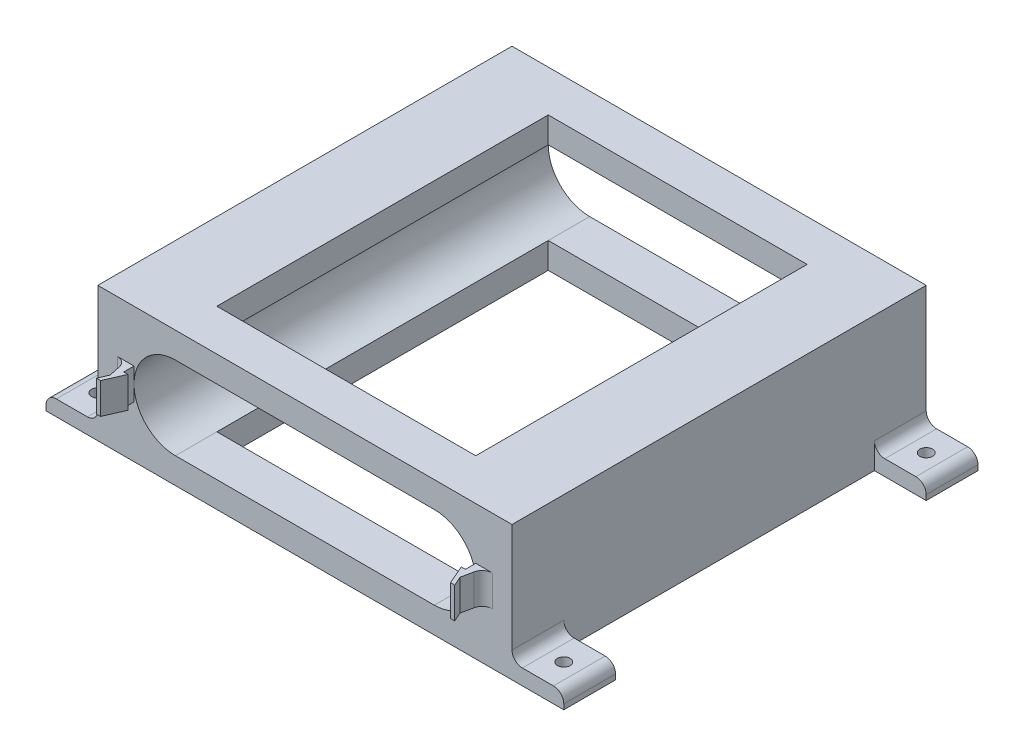
SolidWorks part; units mm, degrees
ref_plane "Front Plane" through (0, 0, 0) normal (0, 0, 1) x (1, 0, 0)
ref_plane "Top Plane" through (0, 0, 0) normal (0, 1, 0) x (1, 0, 0)
ref_plane "Right Plane" through (0, 0, 0) normal (1, 0, 0) x (0, 0, -1)
sketch "Sketch1" plane through (0, 0, 0) normal (0, 0, 1) x (1, 0, 0)
  line L0 (-31.75, 0) -> (31.75, 0) construction
  line L1 (-31.75, 10.16) -> (31.75, 10.16)
  line L2 (-31.75, -10.16) -> (31.75, -10.16)
  line L3 (0, 0) -> (0, 43.3007) construction
  line L4 (50.8, 16.51) -> (-50.8, 16.51)
  line L5 (50.8, 16.51) -> (50.8, -16.51)
  line L6 (50.8, -16.51) -> (-50.8, -16.51)
  line L7 (-50.8, 16.51) -> (-50.8, -16.51)
  arc A0 (-31.75, 10.16) -> (-31.75, -10.16) centre (-31.75, 0) ccw
  arc A1 (31.75, -10.16) -> (31.75, 10.16) centre (31.75, 0) ccw
  point P3 (0, 0)
  point P8 (0, 0)
  point P13 (0, 16.51)
  dimension "D2" = 10.16
  dimension "D3" = 19.05
  dimension "D1" = 63.5
  dimension "D4" = 6.35
  dimension "D5" = 6.35
extrude "Boss-Extrude1" add sketch "Sketch1" against normal blind 101.6
sketch "Sketch2" plane through (0, 16.51, 0) normal (0, 1, 0) x (1, 0, 0)
  line L0 (0, 10.16) -> (0, 91.44) construction
  line L1 (-31.75, 91.44) -> (31.75, 91.44)
  line L2 (-31.75, 91.44) -> (-31.75, 10.16)
  line L3 (-31.75, 10.16) -> (31.75, 10.16)
  line L4 (31.75, 91.44) -> (31.75, 10.16)
  line L5 (50.8, 101.6) -> (-50.8, 101.6) construction
  line L6 (50.8, 0) -> (-50.8, 0) construction
  line L7 (31.75, 101.6) -> (31.75, 0) construction
  point P4 (0, 10.16)
  dimension "D1" = 10.16
  dimension "D2" = 10.16
extrude "Cut-Extrude1" cut sketch "Sketch2" against normal through all
ref_plane "Plane1" through (0, 0, 0) normal (0, 1, 0) x (1, 0, 0)
sketch "Sketch3" plane through (0, 16.51, 0) normal (0, 1, 0) x (1, 0, 0)
  line L1 (-42.926, -4.8679) -> (-43.942, -7.1959)
  line L2 (-43.942, -7.1959) -> (-42.926, -7.1959)
  line L3 (-42.926, -7.1959) -> (-41.91, -4.8679)
  line L8 (-40.894, -2.54) -> (-41.91, -4.8679)
  line L9 (-40.894, -2.54) -> (-41.91, -2.54)
  line L10 (-42.926, -4.8679) -> (-43.942, 0)
  line L11 (-42.926, -2.54) -> (-41.91, -2.54) construction
  line L12 (-41.91, -2.54) -> (-41.91, 0)
  line L13 (50.8, 0) -> (-50.8, 0) construction
  line L14 (-41.91, 101.6) -> (-41.91, 0) construction
  line L15 (-43.942, 0) -> (-41.91, 0)
  line L16 (-42.926, -4.8679) -> (-42.926, 0) construction
  point P3 (-44.2626, 0)
  point P6 (-42.9703, -4.8481)
  dimension "D1" = 1.016
  dimension "D2" = 2.54
  dimension "D3" = 1.016
extrude "Boss-Extrude2" add sketch "Sketch3" along normal mid plane 7.62 from surface at -16.51 starting at plane "Plane1"
fillet "Fillet2" radius 2.54 1 edges at (-43.942, 0, 0)
sketch "Sketch4" plane through (0, -16.51, 0) normal (0, -1, 0) x (1, 0, 0)
  line L0 (0, 0) -> (0, -101.6) construction
  line L1 (-50.8, 0) -> (-63.5, 0)
  line L2 (-50.8, 0) -> (-50.8, -12.7)
  line L3 (-50.8, -12.7) -> (-63.5, -12.7)
  line L4 (-63.5, 0) -> (-63.5, -12.7)
  line L5 (-50.8, -101.6) -> (50.8, -101.6) construction
  line L6 (-50.8, -50.8) -> (50.8, -50.8) construction
  line L7 (-50.8, -101.6) -> (-50.8, 0) construction
  line L8 (50.8, -101.6) -> (50.8, 0) construction
  line L9 (-63.5, -101.6) -> (-63.5, -88.9)
  line L10 (-50.8, -88.9) -> (-63.5, -88.9)
  line L11 (-50.8, -101.6) -> (-50.8, -88.9)
  line L12 (-50.8, -101.6) -> (-63.5, -101.6)
  line L13 (50.8, -101.6) -> (63.5, -101.6)
  line L14 (50.8, -101.6) -> (50.8, -88.9)
  line L15 (50.8, -88.9) -> (63.5, -88.9)
  line L16 (63.5, -101.6) -> (63.5, -88.9)
  line L17 (63.5, 0) -> (63.5, -12.7)
  line L18 (50.8, -12.7) -> (63.5, -12.7)
  line L19 (50.8, 0) -> (50.8, -12.7)
  line L20 (50.8, 0) -> (63.5, 0)
  line L21 (-63.5, 0) -> (-50.8, -12.7) construction
  circle A0 centre (-57.15, -6.35) radius 1.55
  circle A1 centre (57.15, -6.35) radius 1.55
  circle A2 centre (57.15, -95.25) radius 1.55
  circle A3 centre (-57.15, -95.25) radius 1.55
  point P30 (-54.9473, -4.1473)
  point P31 (-57.15, -6.35)
  line M22 (-50.8, 0) -> (-50.8, -101.6)
  line M24 (50.8, -101.6) -> (50.8, 0)
  dimension "D3" = 3.1
  dimension "D1" = 12.7
  dimension "D2" = 12.7
extrude "Boss-Extrude3" add sketch "Sketch4" against normal blind 3.81 contours L12 L10 L9 A3 M22 | L13 L16 L15 A2 M24 | L20 L18 L17 A1 M24 | L1 L4 L3 A0 M22
fillet "Fillet3" radius 2.54 8 edges at (63.5, -12.7, -95.25) (50.8, -12.7, -6.35) (50.8, -12.7, -95.25) (63.5, -12.7, -6.35) (-63.5, -12.7, -95.25) (-50.8, -12.7, -95.25) (-63.5, -12.7, -6.35) (-50.8, -12.7, -6.35)
mirror "Mirror1" about plane through (0, 0, 0) normal (1, 0, 0) of "Fillet2", "Boss-Extrude2"
